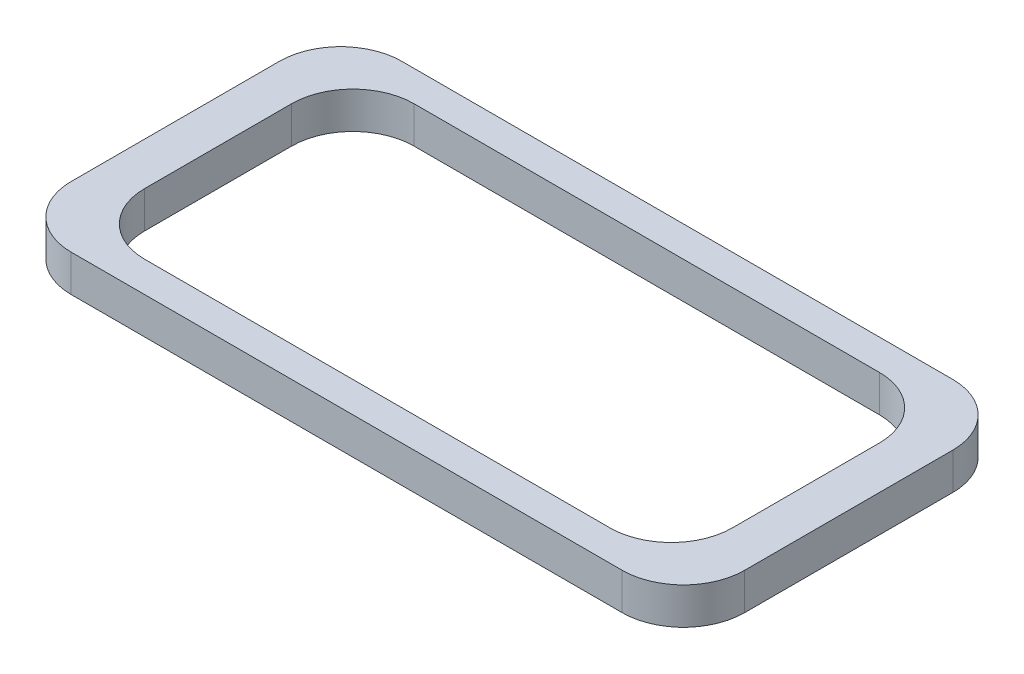
SolidWorks part; units mm, degrees
ref_plane "Front Plane" through (0, 0, 0) normal (0, 0, 1) x (1, 0, 0)
ref_plane "Top Plane" through (0, 0, 0) normal (0, 1, 0) x (1, 0, 0)
ref_plane "Right Plane" through (0, 0, 0) normal (1, 0, 0) x (0, 0, -1)
sketch "Sketch1" plane through (0, 0, 0) normal (0, 1, 0) x (1, 0, 0)
  line L1 (-19, -11) -> (19, -11)
  line L2 (-24, -6) -> (-24, 6)
  line L3 (-19, 11) -> (19, 11)
  line L4 (24, -6) -> (24, 6)
  line L5 (-24, -11) -> (24, 11) construction
  line L6 (-24, 11) -> (24, -11) construction
  line L7 (-22.5, 13.5) -> (22.5, 13.5)
  line L8 (-27.5, 8.5) -> (-27.5, -8.5)
  line L9 (-22.5, -13.5) -> (22.5, -13.5)
  line L10 (27.5, 8.5) -> (27.5, -8.5)
  line L11 (-27.5, 13.5) -> (27.5, -13.5) construction
  line L12 (-27.5, -13.5) -> (27.5, 13.5) construction
  arc A0 (22.5, -13.5) -> (27.5, -8.5) centre (22.5, -8.5) ccw
  arc A1 (22.5, 13.5) -> (27.5, 8.5) centre (22.5, 8.5) cw
  arc A2 (-22.5, 13.5) -> (-27.5, 8.5) centre (-22.5, 8.5) ccw
  arc A3 (-27.5, -8.5) -> (-22.5, -13.5) centre (-22.5, -8.5) ccw
  arc A4 (-19, -11) -> (-24, -6) centre (-19, -6) cw
  arc A5 (19, 11) -> (24, 6) centre (19, 6) cw
  arc A6 (19, -11) -> (24, -6) centre (19, -6) ccw
  arc A7 (-24, 6) -> (-19, 11) centre (-19, 6) cw
  point P0 (0, 0)
  point P5 (0, 0)
  dimension "D5" = 5
  dimension "D1" = 22
  dimension "D2" = 48
  dimension "D3" = 27
  dimension "D4" = 55
extrude "Boss-Extrude1" add sketch "Sketch1" along normal blind 3
